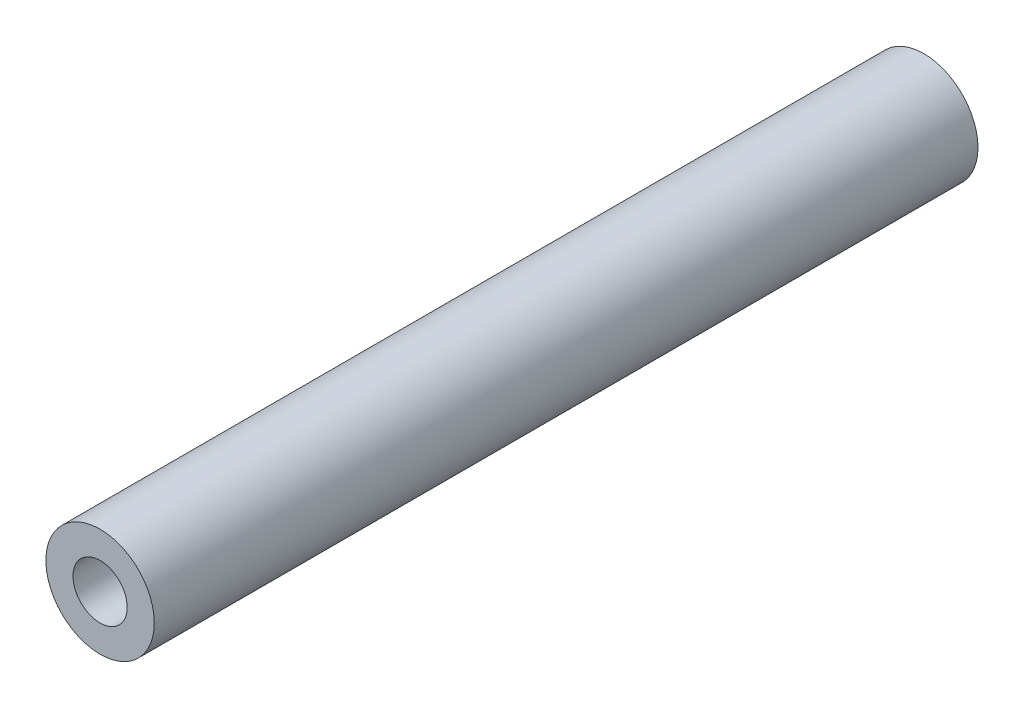
SolidWorks part; units mm, degrees
material "6061 合金"
ref_plane "前视基准面" through (0, 0, 0) normal (0, 0, 1) x (1, 0, 0)
ref_plane "上视基准面" through (0, 0, 0) normal (0, 1, 0) x (1, 0, 0)
ref_plane "右视基准面" through (0, 0, 0) normal (1, 0, 0) x (0, 0, -1)
sketch "草图1" plane through (0, 0, 0) normal (0, 0, 1) x (1, 0, 0)
  circle A1 centre (0, 0) radius 2.5
  dimension "D1" = 5
extrude "凸台-拉伸1" add sketch "草图1" along normal blind 38
hole_wizard "M3 螺纹孔1" positions "草图2" profile "草图3" tap size "M3" standard "GB" end condition through all
sketch "草图2" plane through (0, 0, 38) normal (0, 0, 1) x (1, 0, 0)
  point P0 (0, 0)
sketch "草图3" plane through (0, 0, 38) normal (1, 0, 0) x (0, -1, 0)
  line L0 (0, 0) -> (0, 38)
  line L1 (0, 38) -> (1.25, 38)
  line L2 (1.25, 38) -> (1.25, 0)
  line L5 (1.25, 0) -> (0, 0)
  line L11 (0, -6.35) -> (0, 107.95) construction
  dimension "通孔螺纹孔钻头直径" = 2.5
  dimension "通孔螺纹孔钻头深度" = 38
cosmetic thread "孔螺蚊线1"
